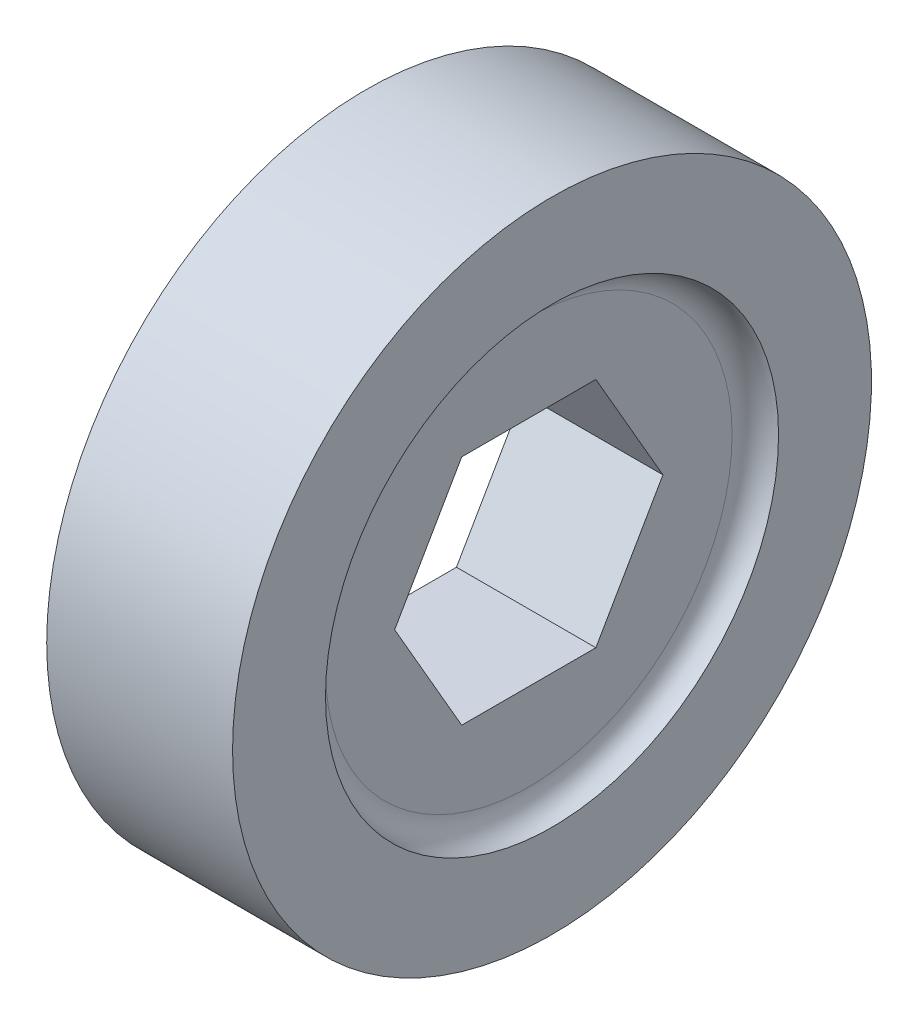
SolidWorks part; units mm, degrees
ref_plane "Front Plane" through (0, 0, 0) normal (0, 0, 1) x (1, 0, 0)
ref_plane "Top Plane" through (0, 0, 0) normal (0, 1, 0) x (1, 0, 0)
ref_plane "Right Plane" through (0, 0, 0) normal (1, 0, 0) x (0, 0, -1)
sketch "Sketch2" plane through (0, 0, 0) normal (0, 0, 1) x (1, 0, 0)
  line L0 (0, 0) -> (0, 17.4625) construction
  line L1 (-5.08, 17.4625) -> (5.08, 17.4625)
  line L2 (5.08, 17.4625) -> (5.08, 12.3825)
  line L3 (3.81, 11.1125) -> (3.81, 0)
  line L4 (-3.81, 11.1125) -> (-3.81, 0)
  line L5 (-5.08, 17.4625) -> (-5.08, 12.3825)
  line L6 (-3.81, 0) -> (3.81, 0)
  line L7 (-6.8694, 0) -> (10.1347, 0) construction
  arc A0 (5.08, 12.3825) -> (3.81, 11.1125) centre (5.08, 11.1125) ccw
  arc A1 (-5.08, 12.3825) -> (-3.81, 11.1125) centre (-5.08, 11.1125) cw
  point P6 (0, 17.4625)
  dimension "D2" = 7.62
  dimension "D1" = 17.4625
  dimension "D3" = 10.16
  dimension "D4" = 12.3825
revolve "Revolve1" add sketch "Sketch2" angle 360 about L7
sketch "Sketch3" plane through (3.81, 0, 0) normal (1, 0, 0) x (0, 0, -1)
  line L1 (7.3323, 0) -> (3.6662, 6.35)
  line L2 (3.6662, 6.35) -> (-3.6662, 6.35)
  line L3 (-3.6662, 6.35) -> (-7.3323, 0)
  line L4 (-7.3323, 0) -> (-3.6662, -6.35)
  line L5 (-3.6662, -6.35) -> (3.6662, -6.35)
  line L6 (3.6662, -6.35) -> (7.3323, 0)
  circle A0 centre (0, 0) radius 6.35 construction
  dimension "D1" = 12.7
extrude "Cut-Extrude1" cut sketch "Sketch3" against normal up to next
